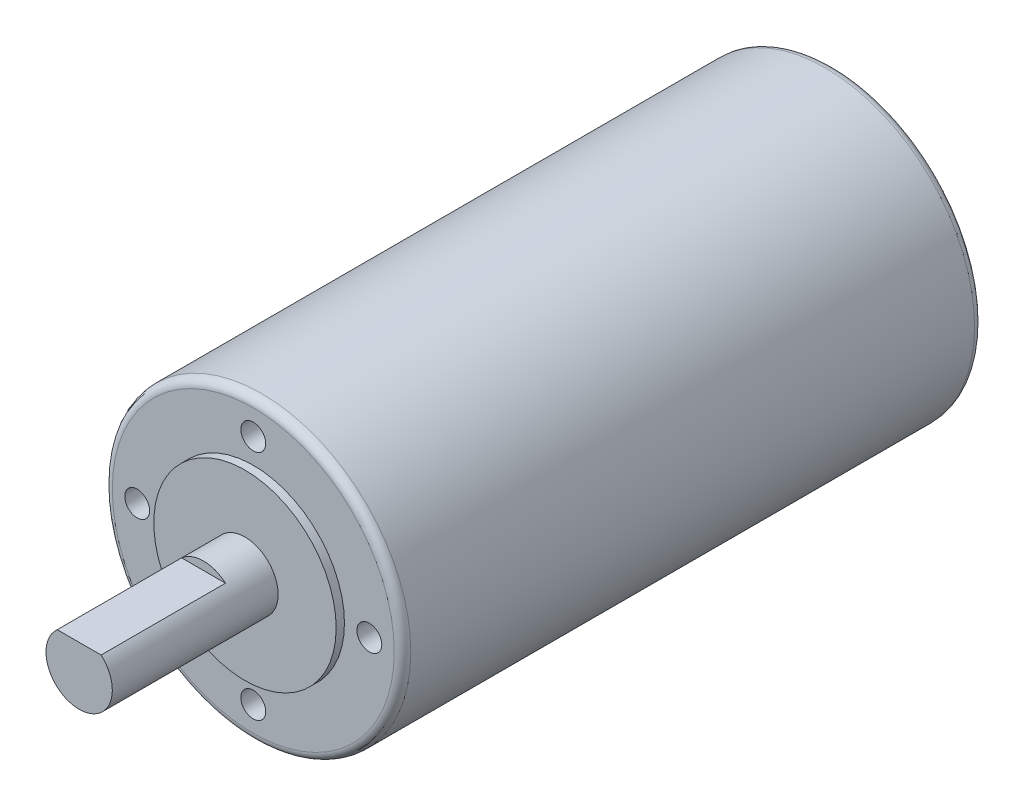
SolidWorks part; units mm, degrees
ref_plane "Front Plane" through (0, 0, 0) normal (0, 0, 1) x (1, 0, 0)
ref_plane "Top Plane" through (0, 0, 0) normal (0, 1, 0) x (1, 0, 0)
ref_plane "Right Plane" through (0, 0, 0) normal (1, 0, 0) x (0, 0, -1)
sketch "Sketch1" plane through (0, 0, 0) normal (0, 0, 1) x (1, 0, 0)
  circle A0 centre (0, 0) radius 18
  circle A1 centre (0, 0) radius 14 construction
  circle A2 centre (0, 14) radius 1.5
  circle A3 centre (14, 0) radius 1.5
  circle A4 centre (0, -14) radius 1.5
  circle A5 centre (-14, 0) radius 1.5
  point P15 (0, 0)
  dimension "D1" = 4
extrude "Gear" add sketch "Sketch1" against normal blind 20
sketch "Sketch2" plane through (0, 0, -20) normal (0, 0, -1) x (-1, 0, 0)
  circle A0 centre (0, 0) radius 18
extrude "Motor" add sketch "Sketch2" along normal blind 50
sketch "Sketch3" plane through (0, 0, -70) normal (0, 0, -1) x (-1, 0, 0)
  circle A0 centre (0, 0) radius 6.5
extrude "Boss-Extrude3" add sketch "Sketch3" along normal blind 3.7
sketch "Sketch4" plane through (0, 0, 0) normal (0, 0, 1) x (1, 0, 0)
  circle A0 centre (0, 0) radius 11
  dimension "D1" = 22
extrude "Boss-Extrude4" add sketch "Sketch4" along normal blind 1
sketch "Sketch5" plane through (0, 0, 1) normal (0, 0, 1) x (1, 0, 0)
  circle A0 centre (0, 0) radius 4
extrude "shaft" add sketch "Sketch5" along normal blind 20
sketch "Sketch6" plane through (0, 0, 21) normal (0, 0, 1) x (1, 0, 0)
  line L0 (-2.6458, 3) -> (2.6458, 3)
  line L1 (0, 4) -> (5.062, 4) construction
  circle A0 centre (0, 0) radius 4 construction
  circle A1 centre (0, 0) radius 4 construction
  circle A2 centre (0, 0) radius 4
  circle M3 centre (0, 0) radius 4
  dimension "D1" = 1
extrude "Cut-Extrude1" cut sketch "Sketch6" against normal blind 15 contours A2 L0 M3
fillet "Fillet1" radius 1 2 edges at (-18, 0, -70) (18, 0, 0)
